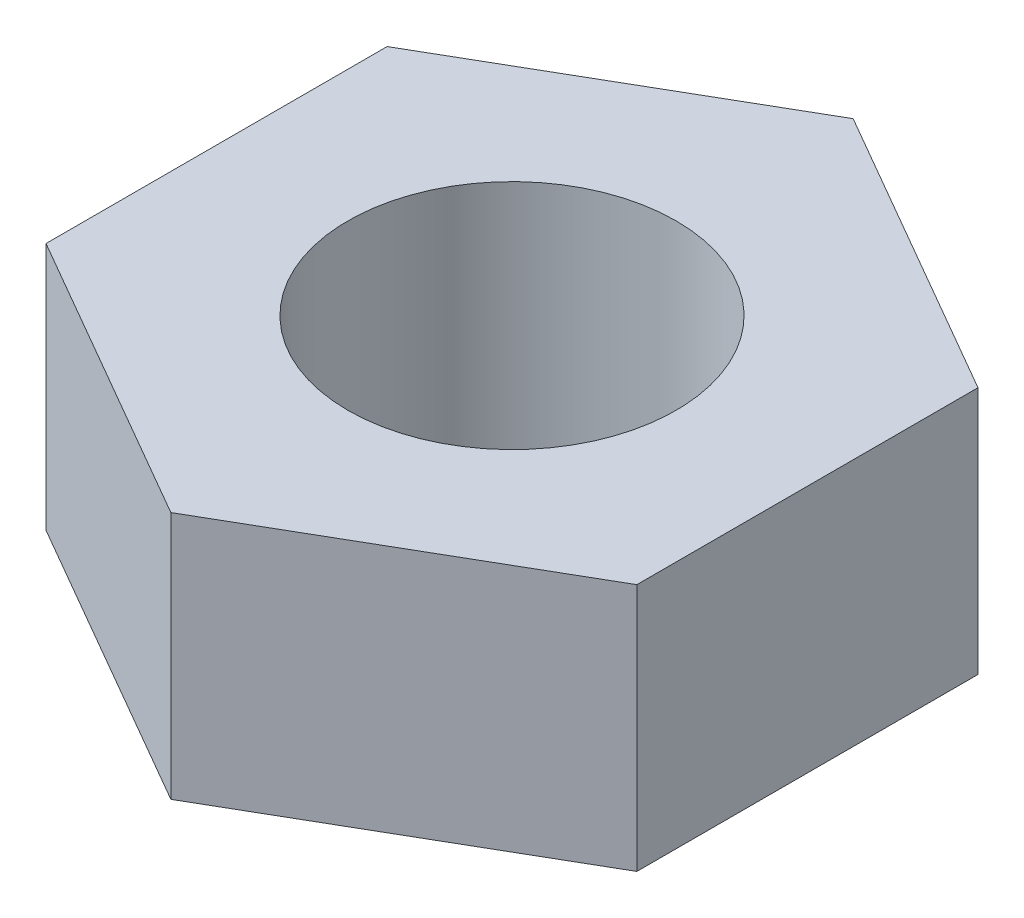
SolidWorks part; units mm, degrees
ref_plane "Front Plane" through (0, 0, 0) normal (0, 0, 1) x (1, 0, 0)
ref_plane "Top Plane" through (0, 0, 0) normal (0, 1, 0) x (1, 0, 0)
ref_plane "Right Plane" through (0, 0, 0) normal (1, 0, 0) x (0, 0, -1)
sketch "Sketch1" plane through (0, 0, 0) normal (0, 1, 0) x (1, 0, 0)
  line L1 (0, -3.1177) -> (2.7, -1.5588)
  line L2 (2.7, -1.5588) -> (2.7, 1.5588)
  line L3 (2.7, 1.5588) -> (0, 3.1177)
  line L4 (0, 3.1177) -> (-2.7, 1.5588)
  line L5 (-2.7, 1.5588) -> (-2.7, -1.5588)
  line L6 (-2.7, -1.5588) -> (0, -3.1177)
  circle A0 centre (0, 0) radius 2.7 construction
  circle A1 centre (0, 0) radius 1.5
  dimension "D2" = 3
  dimension "D1" = 5.4
extrude "Boss-Extrude1" add sketch "Sketch1" along normal blind 2.27
